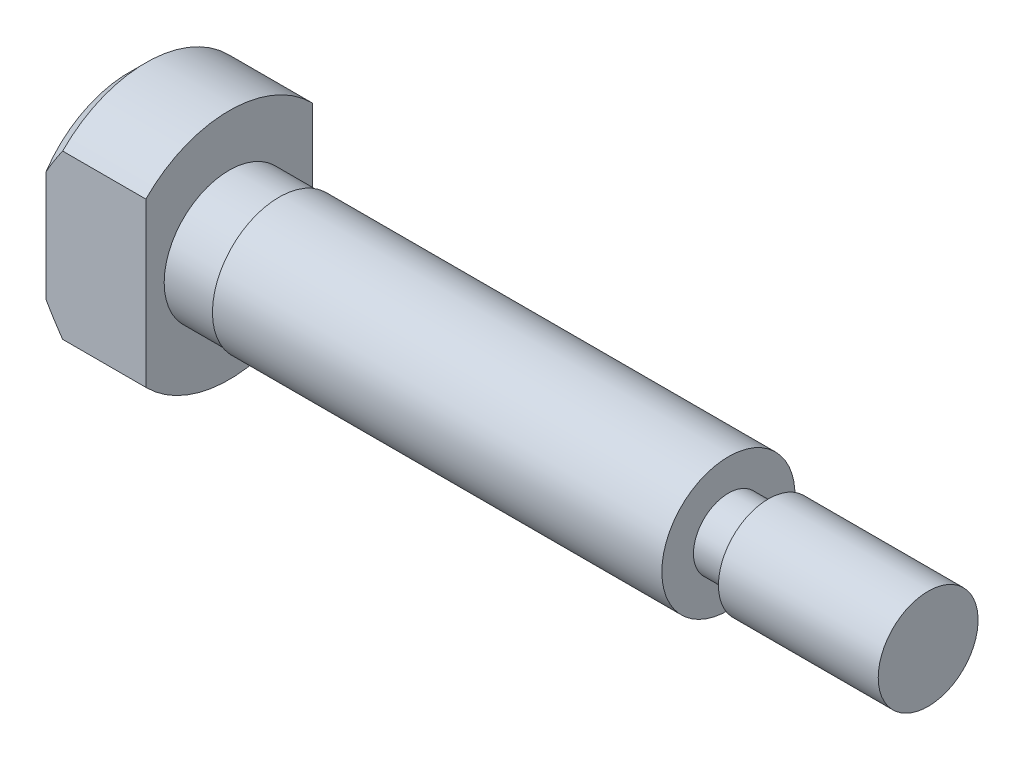
SolidWorks part; units mm, degrees
ref_plane "Front Plane" through (0, 0, 0) normal (0, 0, 1) x (1, 0, 0)
ref_plane "Top Plane" through (0, 0, 0) normal (0, 1, 0) x (1, 0, 0)
ref_plane "Right Plane" through (0, 0, 0) normal (1, 0, 0) x (0, 0, -1)
sketch "Sketch1" plane through (0, 0, 0) normal (0, 0, 1) x (1, 0, 0)
  line L0 (0, 0) -> (21, 0) construction
  line L1 (-3, 0) -> (-3, 3.5)
  line L2 (-3, 3.5) -> (0, 3.5)
  line L3 (0, 3.5) -> (0, 1.95)
  line L4 (0, 1.95) -> (1.5, 1.95)
  line L5 (21, 1.5) -> (21, 0)
  line L6 (-3, 0) -> (21, 0)
  line L7 (1.5, 1.95) -> (1.5, 2)
  line L8 (1.5, 2) -> (15, 2)
  line L9 (15, 2) -> (15, 1.05)
  line L10 (15, 1.05) -> (16.2, 1.05)
  line L11 (16.2, 1.05) -> (16.2, 1.5)
  line L12 (16.2, 1.5) -> (21, 1.5)
  dimension "D" = 4
  dimension "L" = 15
  dimension "A" = 7
  dimension "T" = 3
  dimension "N_s" = 1.5
  dimension "U_s" = 3.9
  dimension "M" = 3
  dimension "F" = 6
  dimension "MSM_1" = 2.1
  dimension "MSM_2" = 1.2
revolve "Revolve1" add sketch "Sketch1" angle 360 about L0
cosmetic thread "Cosmetic Thread1" parameters "TD_s"=2.459
sketch "Sketch2" plane through (0, 0, 0) normal (0, 1, 0) x (1, 0, 0)
  line L1 (-3, 3.5) -> (0, 3.5)
  line L2 (-3, 3.5) -> (-3, 2.5)
  line L3 (-3, 2.5) -> (0, 2.5)
  line L4 (0, 3.5) -> (0, 2.5)
  line L5 (-3, -2.5) -> (0, -2.5)
  line L6 (-3, -2.5) -> (-3, -3.5)
  line L7 (-3, -3.5) -> (0, -3.5)
  line L8 (0, -2.5) -> (0, -3.5)
  line L12 (-3, 3.5) -> (-3, -3.5) construction
  line L13 (0, -3.5) -> (0, 3.5) construction
  line L14 (0, 0) -> (-3, 0) construction
  dimension "B" = 5
  dimension "A" = 7
extrude "Cut-Extrude1" cut sketch "Sketch2" against normal through all and the other way through all
chamfer "Chamfer1" distance 0.5 angle 45 2 edges at (-3, -3.5, 0) (-3, 3.5, 0)
sketch "Sketch3" [suppressed] plane through (0, 0, 0) normal (0, 0, 1) x (1, 0, 0)
  line L0 (15, -3) -> (15, 3) construction
  line L2 (15, 3) -> (24, 3)
  line L3 (15, 3) -> (15, 0)
  line L4 (15, 0) -> (24, 0)
  line L5 (24, 3) -> (24, 0)
  line L6 (0, 0) -> (24, 0) construction
  line L10 (24, -2.5) -> (24, 2.5) construction
  dimension "D" = 4
revolve "Cut-Revolve1" [suppressed] cut sketch "Sketch3" angle 360 about L6
sketch "Sketch4" [suppressed] plane through (0, 0, 0) normal (0, 0, 1) x (1, 0, 0)
  line L0 (0, 0) -> (20, 0) construction
  line L1 (15, 2.05) -> (16.2, 2.05)
  line L2 (16.2, 2.05) -> (16.2, 2.5)
  line L3 (16.2, 2.5) -> (20, 2.5)
  line L4 (20, 2.5) -> (20, 0)
  line L5 (20, 0) -> (15, 0)
  line L6 (15, 0) -> (15, 2.05)
  line L7 (15, -3) -> (15, 3) construction
  line L8 (24, 2.5) -> (24, 0) construction
  line L9 (15, 2.05) -> (16.2, 2.05) construction
  dimension "FC" = 5
revolve "Revolve2" [suppressed] add sketch "Sketch4" angle 360 about L0
cosmetic thread "Cosmetic Thread2" [suppressed] parameters "TD_s"=4.11
sketch "Sketch5" [suppressed] plane through (0, 0, 0) normal (0, 0, 1) x (1, 0, 0)
  line L1 (15, -3) -> (15, 3) construction
  line L2 (15, 3) -> (30, 3)
  line L3 (15, 3) -> (15, 0)
  line L4 (15, 0) -> (30, 0)
  line L5 (30, 3) -> (30, 0)
  line L6 (0, 0) -> (30, 0) construction
  dimension "D1" = 9
  dimension "D" = 4
revolve "Cut-Revolve2" [suppressed] cut sketch "Sketch5" angle 360 about L6
sketch "Sketch6" [suppressed] plane through (0, 0, 0) normal (0, 0, 1) x (1, 0, 0)
  line L0 (0, 0) -> (24, 0) construction
  line L1 (15, 1.55) -> (16.2, 1.55)
  line L2 (16.2, 1.55) -> (16.2, 2)
  line L3 (16.2, 2) -> (24, 2)
  line L4 (24, 2) -> (24, 0)
  line L5 (24, 0) -> (15, 0)
  line L6 (15, 0) -> (15, 1.55)
  line L10 (15, -3) -> (15, 3) construction
  dimension "F" = 6
  dimension "MSM_4" = 1.2
  dimension "MSM_3" = 3.1
  dimension "MC" = 4
revolve "Revolve3" [suppressed] add sketch "Sketch6" angle 360 about L0
cosmetic thread "Cosmetic Thread3" [suppressed] parameters "TD_s"=3.22
sketch "Sketch7" [suppressed] plane through (0, 0, 0) normal (0, 0, 1) x (1, 0, 0)
  line L0 (0, 0) -> (20, 0) construction
  line L1 (15, 1.55) -> (16.2, 1.55)
  line L2 (16.2, 1.55) -> (16.2, 2)
  line L3 (16.2, 2) -> (20, 2)
  line L4 (20, 2) -> (20, 0)
  line L5 (20, 0) -> (15, 0)
  line L6 (15, 0) -> (15, 1.55)
  line L7 (15, -3) -> (15, 3) construction
  dimension "FC" = 5
  dimension "MSM_3" = 3.1
  dimension "MC" = 4
  dimension "MSM_4" = 1.2
revolve "Revolve4" [suppressed] add sketch "Sketch7" angle 360 about L0
cosmetic thread "Cosmetic Thread4" [suppressed] parameters "TD_s"=3.22
sketch "Sketch8" [suppressed] plane through (0, 0, 0) normal (0, 0, 1) x (1, 0, 0)
  line L0 (0, 0) -> (-5, 0) construction
  line L1 (-5, 5) -> (0, 5)
  line L2 (-5, 5) -> (-5, 0)
  line L3 (-5, 0) -> (0, 0)
  line L4 (0, 5) -> (0, 0)
  line L6 (0, 5) -> (0, 2.9) construction
  line L7 (-5, 0) -> (-5, 5) construction
  dimension "A" = 7
revolve "Cut-Revolve3" [suppressed] cut sketch "Sketch8" angle 360 about L0
sketch "Sketch9" [suppressed] plane through (0, 0, 0) normal (0, 0, 1) x (1, 0, 0)
  line L0 (0, 0) -> (-2, 0) construction
  line L1 (-2, 5) -> (0, 5)
  line L2 (-2, 5) -> (-2, 0)
  line L3 (-2, 0) -> (0, 0)
  line L4 (0, 5) -> (0, 0)
  line L5 (0, 2.9) -> (0, -2.9) construction
  dimension "TC" = 2
  dimension "A" = 7
revolve "Revolve5" [suppressed] add sketch "Sketch9" angle 360 about L0
sketch "Sketch10" [suppressed] plane through (0, 0, 0) normal (0, 1, 0) x (1, 0, 0)
  line L1 (-2, -4) -> (0, -4)
  line L2 (-2, -4) -> (-2, -5)
  line L3 (-2, -5) -> (0, -5)
  line L4 (0, -4) -> (0, -5)
  line L5 (-2, 5) -> (0, 5)
  line L6 (-2, 5) -> (-2, 4)
  line L7 (-2, 4) -> (0, 4)
  line L8 (0, 5) -> (0, 4)
  line L9 (0, 0) -> (-2, 0) construction
  line L10 (-2, 5) -> (-2, -5) construction
  line L13 (0, -5) -> (0, 5) construction
  dimension "A" = 7
  dimension "B" = 5
extrude "Cut-Extrude2" [suppressed] cut sketch "Sketch10" against normal through all and the other way through all
chamfer "Chamfer2" [suppressed] distance 0.5 angle 45
equation "\"D1@Sketch5\"= \"M@Sketch1\"*3"
